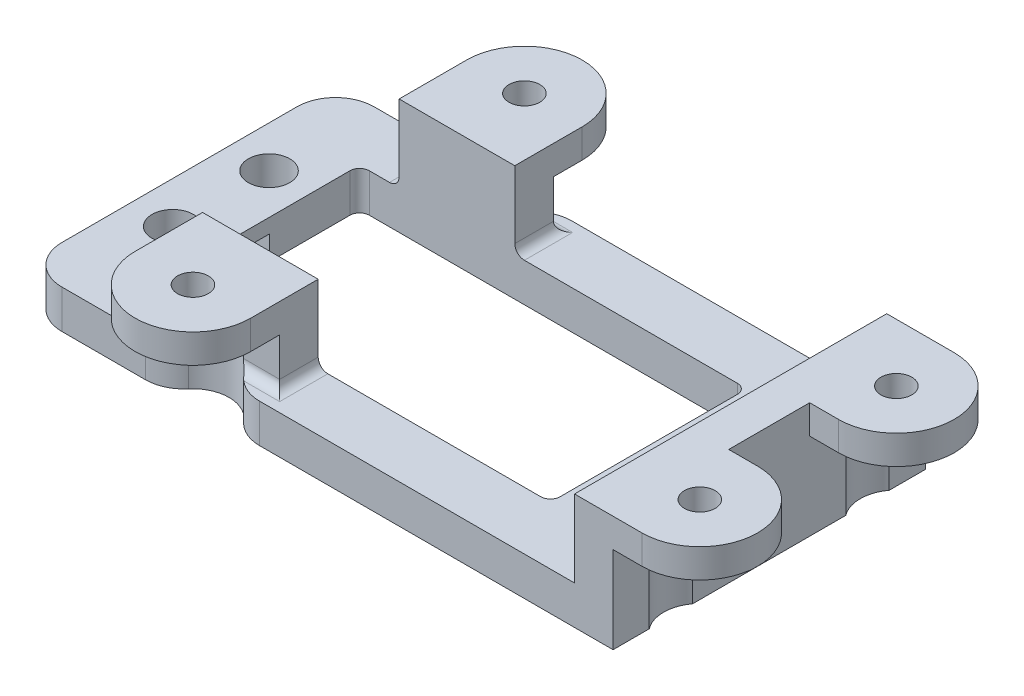
SolidWorks part; units mm, degrees
ref_plane "Front Plane" through (0, 0, 0) normal (0, 0, 1) x (1, 0, 0)
ref_plane "Top Plane" through (0, 0, 0) normal (0, 1, 0) x (1, 0, 0)
ref_plane "Right Plane" through (0, 0, 0) normal (1, 0, 0) x (0, 0, -1)
sketch "Sketch1" plane through (0, 0, 0) normal (0, 1, 0) x (1, 0, 0)
  line L1 (-20.1, -10.2) -> (20.1, -10.2)
  line L2 (-20.1, -10.2) -> (-20.1, 10.2)
  line L3 (-20.1, 10.2) -> (20.1, 10.2)
  line L4 (20.1, -10.2) -> (20.1, 10.2)
  line L5 (0, 10.2) -> (0, -10.2) construction
  line L6 (-20.1, 0) -> (20.1, 0) construction
  line L7 (-28.6, -16.2) -> (28.6, -16.2)
  line L8 (-28.6, -16.2) -> (-28.6, 16.2)
  line L9 (-28.6, 16.2) -> (28.6, 16.2)
  line L10 (28.6, -16.2) -> (28.6, 16.2)
  line L11 (0, 16.2) -> (0, -16.2) construction
  line L12 (-28.6, 0) -> (28.6, 0) construction
  point P8 (0, 0)
  point P224 (0, 0)
  point P426 (0, 0)
  dimension "D1" = 40.2
  dimension "D2" = 20.4
  dimension "D3" = 8.5
  dimension "D4" = 6
extrude "Boss-Extrude1" add sketch "Sketch1" along normal blind 4
fillet "Fillet1" radius 1 4 edges at (-20.1, 2, 10.2) (20.1, 2, 10.2) (20.1, 2, -10.2) (-20.1, 2, -10.2)
sketch "Sketch2" plane through (0, 4, 0) normal (0, 1, 0) x (1, 0, 0)
  line L0 (-24.3, 0) -> (24.3, 0) construction
  line L1 (-24.3, -5) -> (-24.3, 5) construction
  line L2 (24.3, 5) -> (24.3, -5) construction
  circle A0 centre (-24.3, 5) radius 2.15
  circle A1 centre (-24.3, -5) radius 2.15
  circle A2 centre (24.3, -5) radius 2.15
  circle A3 centre (24.3, 5) radius 2.15
  dimension "D3" = 4.3
  dimension "D4" = 4.3
  dimension "D5" = 4.3
  dimension "D6" = 4.3
  dimension "D1" = 10
  dimension "D2" = 48.6
extrude "Cut-Extrude1" cut sketch "Sketch2" against normal through all
ref_plane "Plane1" through (0, 0, 0) normal (0, 0, 1) x (1, 0, 0)
sketch "Sketch3" plane through (0, 0, 0) normal (0, 0, 1) x (1, 0, 0)
  line L0 (-26.5, 0) -> (-26.5, 0.7)
  line L1 (-28.6, 0) -> (28.6, 0) construction
  line L2 (-26.5, 0.7) -> (-21.2, 2.5)
  line L3 (-21.2, 2.5) -> (-20.1, 2.5)
  line L4 (-20.1, 2.5) -> (-20.1, 0)
  line L5 (-20.1, 0) -> (-26.5, 0)
  line L6 (-20.1, 4) -> (-20.1, 0) construction
  dimension "D1" = 2.5
  dimension "D2" = 0.7
  dimension "D3" = 6.4
  dimension "D4" = 1.1
extrude "Cut-Extrude2" cut sketch "Sketch3" against normal mid plane 1.7
ref_plane "Plane2" through (0, 0, 0) normal (1, 0, 0) x (0, 0, -1)
mirror "Mirror1" about plane through (0, 0, 0) normal (1, 0, 0) of "Cut-Extrude2"
sketch "Sketch5" plane through (0, 4, 0) normal (0, 1, 0) x (1, 0, 0)
  line L5 (0, -2.2) -> (0, 2.2) construction
  line L8 (-19.1, -10.2) -> (19.1, -10.2) construction
  line L9 (-16, -10.2) -> (-4, -10.2)
  line L10 (-16, -10.2) -> (-16, -14.2)
  line L11 (-16, -14.2) -> (-4, -14.2)
  line L12 (-4, -10.2) -> (-4, -14.2)
  line L13 (-10, -14.2) -> (-10, -10.2) construction
  line L14 (-16, -12.2) -> (-4, -12.2) construction
  point P0 (-10, -12.2)
  point P16 (-12.3747, -13.2)
  point P84 (-10, -12.2)
  dimension "D1" = 10
  dimension "D2" = 12
  dimension "D3" = 4
extrude "Boss-Extrude2" add sketch "Sketch5" along normal blind 8
sketch "Sketch6" plane through (0, 12, 0) normal (0, 1, 0) x (1, 0, 0)
  line L0 (-16, -14.2) -> (-4, -14.2)
  line L1 (-4, -14.2) -> (-4, -17.2)
  line L2 (-4, -17.2) -> (-16, -17.2) construction
  line L3 (-16, -17.2) -> (-16, -14.2)
  arc A0 (-16, -17.2) -> (-4, -17.2) centre (-10, -17.2) ccw
  circle A1 centre (-10, -17.2) radius 1.6
  dimension "D2" = 3.2
  dimension "D1" = 3
extrude "Boss-Extrude3" add sketch "Sketch6" against normal blind 3
sketch "Sketch7" plane through (0, 0, 0) normal (0, -1, 0) x (1, 0, 0)
  circle A0 centre (-10, 17.2) radius 3.75
  circle A1 centre (-10, 17.2) radius 1.6 construction
  dimension "D1" = 7.5
extrude "Cut-Extrude3" cut sketch "Sketch7" against normal up to surface (9 mm away) up to face at (-10, 9, 18.8)
mirror "Mirror4" about plane through (0, 0, 0) normal (0, 0, 1) of "Cut-Extrude3", "Boss-Extrude3", "Boss-Extrude2"
fillet "Fillet4" radius 4 6 edges at (-28.6, 2, -16.2) (-6.3858, 2, -16.2) (-13.6142, 2, -16.2) (-13.6142, 2, 16.2) (-6.3858, 2, 16.2) (-28.6, 2, 16.2)
fillet "Fillet6" radius 1 8 edges at (-14.125, 4, 14.2) (-16, 4, 12.2) (-5.875, 4, -14.2) (-14.125, 4, -14.2) (-4, 4, -12.2) (-16, 4, -12.2) (-4, 4, 12.2) (-5.875, 4, 14.2)
sketch "Sketch8" plane through (0, 0, 0) normal (0, -1, 0) x (1, 0, 0)
  line L1 (28.6, -16.2) -> (32.6, -16.2)
  line L2 (28.6, -16.2) -> (28.6, 16.2)
  line L3 (28.6, 16.2) -> (32.6, 16.2)
  line L4 (32.6, -16.2) -> (32.6, 16.2)
  line L5 (30.6, 16.2) -> (30.6, -16.2) construction
  line L6 (28.6, 0) -> (32.6, 0) construction
  point P4 (0, 0)
  point P388 (30.6, 0)
  dimension "D1" = 4
extrude "Boss-Extrude4" add sketch "Sketch8" against normal up to surface (12 mm away)
sketch "Sketch9" plane through (0, 12, 0) normal (0, 1, 0) x (1, 0, 0)
  line L0 (32.6, -16.2) -> (32.6, -4.2)
  line L1 (32.6, 16.2) -> (32.6, -16.2) construction
  line L2 (32.6, -4.2) -> (35.6, -4.2)
  line L4 (35.6, -16.2) -> (32.6, -16.2)
  line L6 (35.6, -16.2) -> (35.6, -4.2) construction
  arc A0 (35.6, -16.2) -> (35.6, -4.2) centre (35.6, -10.2) ccw
  circle A2 centre (35.6, -10.2) radius 1.6
  dimension "D2" = 3.2
  dimension "D1" = 12
  dimension "D3" = 3
extrude "Boss-Extrude6" add sketch "Sketch9" against normal up to surface (3 mm away) up to face at (-10, 9, 16.075)
sketch "Sketch10" plane through (0, 0, 0) normal (0, -1, 0) x (1, 0, 0)
  circle A0 centre (35.6, 10.2) radius 3.75
  circle A1 centre (35.6, 10.2) radius 1.6 construction
  point P2 (0, 0)
  dimension "D1" = 7.5
extrude "Cut-Extrude4" cut sketch "Sketch10" against normal up to surface (9 mm away) up to face at (35.6, 9, 10.2)
mirror "Mirror5" about plane through (0, 0, 0) normal (0, 0, 1) of "Cut-Extrude4", "Boss-Extrude6"
equation "\"D4@Sketch2\"=\"D3@Sketch2\""
equation "\"D5@Sketch2\"=\"D3@Sketch2\""
equation "\"D6@Sketch2\"=\"D3@Sketch2\""
